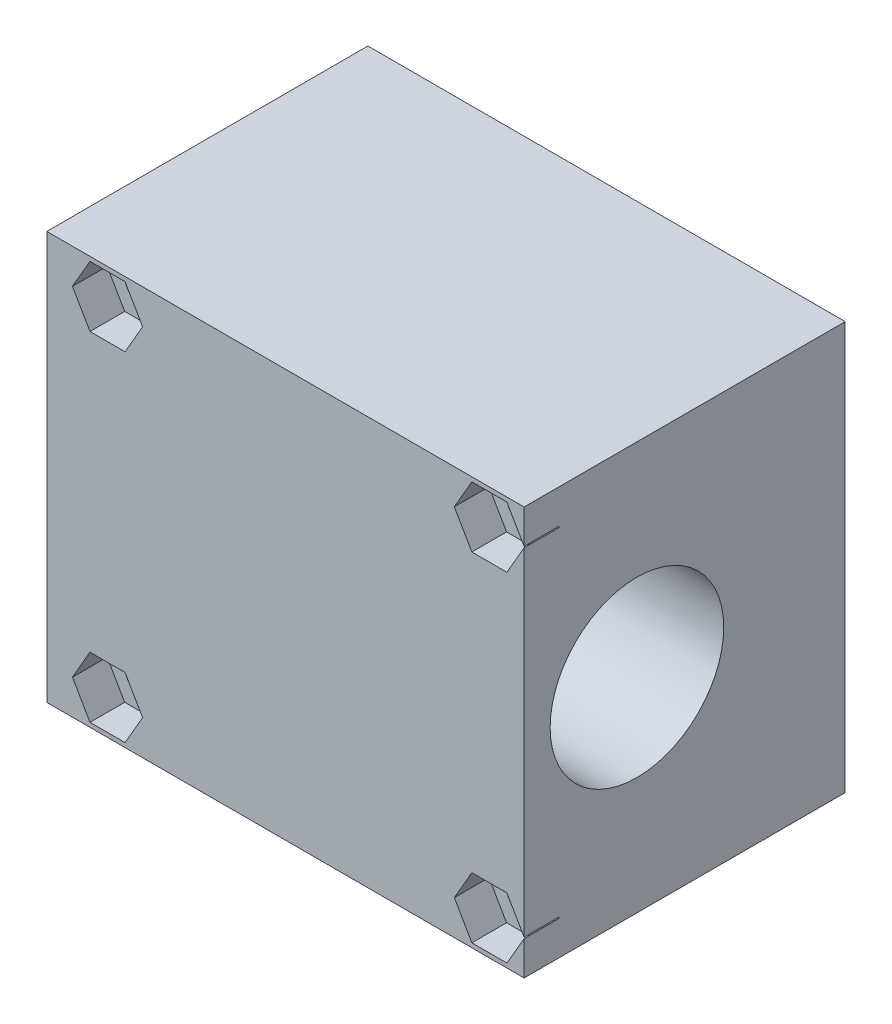
SolidWorks part; units mm, degrees
ref_plane "Plan de face" through (0, 0, 0) normal (0, 0, 1) x (1, 0, 0)
ref_plane "Plan de dessus" through (0, 0, 0) normal (0, 1, 0) x (1, 0, 0)
ref_plane "Plan de droite" through (0, 0, 0) normal (1, 0, 0) x (0, 0, -1)
sketch "Esquisse1" plane through (0, 0, 0) normal (0, 0, 1) x (1, 0, 0)
  line L1 (0, 0) -> (55, 0)
  line L2 (0, 0) -> (0, 47)
  line L3 (0, 47) -> (55, 47)
  line L4 (55, 0) -> (55, 47)
  dimension "D1" = 47
  dimension "D2" = 55
extrude "Boss.-Extru.1" add sketch "Esquisse1" along normal blind 37
sketch "Esquisse2" plane through (0, 0, 0) normal (0, 0, -1) x (-1, 0, 0)
  line L0 (-55, 0) -> (-55, 47) construction
  line L1 (-55, 47) -> (0, 47) construction
  line L2 (0, 0) -> (-55, 0) construction
  line L3 (0, 47) -> (0, 0) construction
  circle A0 centre (-51, 43) radius 2
  circle A1 centre (-7, 43) radius 2
  circle A2 centre (-7, 4) radius 2
  circle A3 centre (-51, 4) radius 2
  dimension "D1" = 4
  dimension "D2" = 4
  dimension "D3" = 4
  dimension "D4" = 4
  dimension "D5" = 4
  dimension "D6" = 4
  dimension "D7" = 4
  dimension "D8" = 4
  dimension "D9" = 4
  dimension "D10" = 4
  dimension "D11" = 7
  dimension "D12" = 7
extrude "Enlèv. mat.-Extru.1" cut sketch "Esquisse2" against normal through all contours A2 | A3 | A0 | A1
sketch "Esquisse3" plane through (0, 0, 0) normal (0, 0, -1) x (-1, 0, 0)
  line L0 (-55, 0) -> (-55, 47) construction
  line L1 (-54, 46) -> (-4, 46)
  line L2 (-54, 46) -> (-54, 1)
  line L3 (-54, 1) -> (-4, 1)
  line L4 (-4, 46) -> (-4, 1)
  line L5 (0, 0) -> (-55, 0) construction
  line L6 (-55, 47) -> (0, 47) construction
  dimension "D1" = 1
  dimension "D2" = 1
  dimension "D3" = 1
  dimension "D4" = 50
extrude "Enlèv. mat.-Extru.2" cut sketch "Esquisse3" against normal blind 1
sketch "Esquisse4" plane through (0, 0, 1) normal (0, 0, -1) x (-1, 0, 0)
  line L0 (-54, 46) -> (-54, 1) construction
  line L1 (-53, 2) -> (-5, 2)
  line L2 (-53, 2) -> (-53, 45)
  line L3 (-53, 45) -> (-5, 45)
  line L4 (-5, 2) -> (-5, 45)
  line L5 (-4, 46) -> (-54, 46) construction
  line L6 (-4, 1) -> (-4, 46) construction
  line L7 (-54, 1) -> (-4, 1) construction
  dimension "D1" = 1
  dimension "D2" = 1
  dimension "D3" = 1
  dimension "D4" = 1
extrude "Enlèv. mat.-Extru.3" cut sketch "Esquisse4" against normal blind 10
sketch "Esquisse5" plane through (55, 0, 0) normal (1, 0, 0) x (0, 0, -1)
  line L0 (-37, 0) -> (0, 0) construction
  line L1 (-37, 0) -> (-37, 47) construction
  circle A0 centre (-24, 23.5) radius 10
  dimension "D1" = 20
  dimension "D2" = 23.5
  dimension "D3" = 13
extrude "Enlèv. mat.-Extru.4" cut sketch "Esquisse5" against normal blind 40
sketch "Esquisse6" plane through (0, 0, 0) normal (-1, 0, 0) x (0, 0, 1)
  line L0 (37, 47) -> (37, 0) construction
  line L1 (14, 33.5) -> (34, 33.5)
  line L2 (14, 33.5) -> (14, 13.5)
  line L3 (14, 13.5) -> (34, 13.5)
  line L4 (34, 33.5) -> (34, 13.5)
  line L5 (37, 47) -> (0, 47) construction
  dimension "D1" = 20
  dimension "D2" = 20
  dimension "D3" = 3
  dimension "D4" = 13.5
extrude "Enlèv. mat.-Extru.5" cut sketch "Esquisse6" against normal blind 10
sketch "Esquisse7" plane through (0, 0, 11) normal (0, 0, -1) x (-1, 0, 0)
  line L0 (-55, 47) -> (0, 47) construction
  line L1 (-5, 33.5) -> (-10, 33.5)
  line L2 (-5, 33.5) -> (-5, 13.5)
  line L3 (-5, 13.5) -> (-10, 13.5)
  line L4 (-10, 33.5) -> (-10, 13.5)
  line L5 (-5, 4) -> (-5, 43) construction
  dimension "D1" = 20
  dimension "D2" = 13.5
  dimension "D3" = 0
  dimension "D4" = 5
extrude "Enlèv. mat.-Extru.6" cut sketch "Esquisse7" against normal blind 4
sketch "Esquisse10" plane through (15, 0, 0) normal (1, 0, 0) x (0, 0, -1)
  circle A0 centre (-24, 23.5) radius 2.5
  circle A1 centre (-19.5, 28) radius 2.5
  circle A2 centre (-19.5, 19) radius 2.5
  circle A3 centre (-28.5, 19) radius 2.5
  circle A4 centre (-28.5, 28) radius 2.5
  circle A5 centre (-24, 23.5) radius 10 construction
  dimension "D1" = 5
  dimension "D2" = 5
  dimension "D3" = 5
  dimension "D4" = 5
  dimension "D5" = 5
  dimension "D6" = 0
  dimension "D7" = 9
  dimension "D8" = 9
  dimension "D9" = 9
  dimension "D10" = 9
  dimension "D11" = 4.5
  dimension "D12" = 4.5
  dimension "D13" = 0
  dimension "D14" = 0
extrude "Enlèv. mat.-Extru.7" cut sketch "Esquisse10" against normal through all
sketch "Esquisse11" plane through (0, 0, 37) normal (0, 0, 1) x (1, 0, 0)
  line L1 (11.0415, 43) -> (9.0207, 46.5)
  line L2 (9.0207, 46.5) -> (4.9793, 46.5)
  line L3 (4.9793, 46.5) -> (2.9585, 43)
  line L4 (2.9585, 43) -> (4.9793, 39.5)
  line L5 (4.9793, 39.5) -> (9.0207, 39.5)
  line L6 (9.0207, 39.5) -> (11.0415, 43)
  line L7 (46.9585, 43) -> (48.9793, 39.5)
  line L8 (48.9793, 39.5) -> (53.0207, 39.5)
  line L9 (53.0207, 39.5) -> (55.0415, 43)
  line L10 (55.0415, 43) -> (53.0207, 46.5)
  line L11 (53.0207, 46.5) -> (48.9793, 46.5)
  line L12 (48.9793, 46.5) -> (46.9585, 43)
  line L13 (46.9585, 4) -> (48.9793, 0.5)
  line L14 (48.9793, 0.5) -> (53.0207, 0.5)
  line L15 (53.0207, 0.5) -> (55.0415, 4)
  line L16 (55.0415, 4) -> (53.0207, 7.5)
  line L17 (53.0207, 7.5) -> (48.9793, 7.5)
  line L18 (48.9793, 7.5) -> (46.9585, 4)
  line L19 (11.0415, 4) -> (9.0207, 7.5)
  line L20 (9.0207, 7.5) -> (4.9793, 7.5)
  line L21 (4.9793, 7.5) -> (2.9585, 4)
  line L22 (2.9585, 4) -> (4.9793, 0.5)
  line L23 (4.9793, 0.5) -> (9.0207, 0.5)
  line L24 (9.0207, 0.5) -> (11.0415, 4)
  circle A0 centre (7, 43) radius 3.5 construction
  circle A1 centre (51, 43) radius 3.5 construction
  circle A2 centre (51, 4) radius 3.5 construction
  circle A3 centre (7, 4) radius 3.5 construction
  dimension "D1" = 7
  dimension "D2" = 7
  dimension "D3" = 7
  dimension "D4" = 7
extrude "Enlèv. mat.-Extru.8" cut sketch "Esquisse11" against normal blind 4
